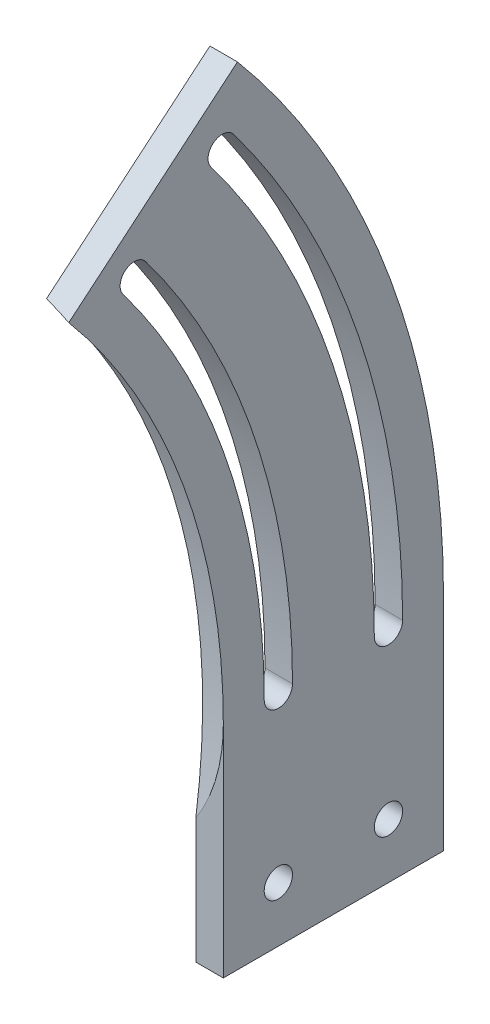
SolidWorks part; units mm, degrees
material "ABS"
ref_plane "Front Plane" through (0, 0, 0) normal (0, 0, 1) x (1, 0, 0)
ref_plane "Top Plane" through (0, 0, 0) normal (0, 1, 0) x (1, 0, 0)
ref_plane "Right Plane" through (0, 0, 0) normal (1, 0, 0) x (0, 0, -1)
sketch "Sketch1" plane through (0, 0, 0) normal (1, 0, 0) x (0, 0, -1)
  line L0 (-1000, 0) -> (49000, 0) construction
  line L1 (0, 0) -> (116.7452, 97.9608) construction
  line L2 (0, 0) -> (71.9216, -52.2541) construction
  line L3 (152.4, 0) -> (152.4, -50.8)
  line L5 (152.4, -50.8) -> (203.2, -50.8)
  line L6 (203.2, -50.8) -> (203.2, 0)
  line L7 (8.1928, 2.9819) -> (218.3104, 79.4585) construction
  line L10 (116.7452, 97.9608) -> (155.6602, 130.6144)
  line L13 (226.7478, 82.5295) -> (220.7808, 80.3576) construction
  line L14 (220.7808, 80.3576) -> (46992.8239, 17103.9891) construction
  arc A0 (152.4, 0) -> (116.7452, 97.9608) centre (0, 0) ccw
  arc A4 (155.6602, 130.6144) -> (203.2, 0) centre (0, 0) cw
  point P9 (226.7478, 82.5295)
  point P15 (0, 0)
  dimension "D1" = 304.8
  dimension "D2" = 40
  dimension "D3" = 36
  dimension "D4" = 50.8
  dimension "D5" = 50.8
  dimension "D6" = 20
  dimension "D9" = 6.35
extrude "Boss-Extrude1" add sketch "Sketch1" along normal blind 6.35
sketch "Sketch2" plane through (6.35, 0, 0) normal (1, 0, 0) x (0, 0, -1)
  line L0 (-1000, 0) -> (49000, 0) construction
  line L1 (0, 0) -> (182.5681, 137.5749) construction
  arc A1 (152.4, 0) -> (116.7452, 97.9608) centre (0, 0) ccw construction
  arc A2 (134.4614, 101.3239) -> (129.2481, 97.3954) centre (131.8547, 99.3597) ccw
  arc A3 (129.2481, 97.3954) -> (161.8361, 0) centre (0, 0) cw
  arc A4 (134.4614, 101.3239) -> (168.3639, 0) centre (0, 0) cw
  arc A5 (161.8361, 0) -> (168.3639, 0) centre (165.1, 0) ccw
  arc A6 (154.7467, 116.61) -> (149.5334, 112.6815) centre (152.1401, 114.6458) ccw
  arc A7 (149.5334, 112.6815) -> (187.2361, 0) centre (0, 0) cw
  arc A8 (154.7467, 116.61) -> (193.7639, 0) centre (0, 0) cw
  arc A9 (152.1401, 114.6458) -> (190.5, 0) centre (0, 0) cw construction
  arc A10 (187.2361, 0) -> (193.7639, 0) centre (190.5, 0) ccw
  point P9 (131.8547, 99.3597)
  point P14 (152.1401, 114.6458)
  point P19 (165.1, 0)
  dimension "D3" = 6.5278
  dimension "D5" = 6.5278
  dimension "D1" = 37
  dimension "D2" = 165.1
  dimension "D4" = 25.4
extrude "Cut-Extrude4" cut sketch "Sketch2" against normal blind 6.35
sketch "Sketch3" plane through (6.35, 0, 0) normal (1, 0, 0) x (0, 0, -1)
  line L0 (165.1, -38.1) -> (190.5, -38.1) construction
  line L1 (152.4, -50.8) -> (165.1, -50.8) construction
  line L2 (152.4, -50.8) -> (152.4, -38.1) construction
  line L3 (152.4, -38.1) -> (165.1, -38.1) construction
  line L4 (165.1, -50.8) -> (165.1, -38.1) construction
  circle A0 centre (165.1, -38.1) radius 3.2639
  circle A1 centre (190.5, -38.1) radius 3.2639
  dimension "D3" = 6.5278
  dimension "D5" = 6.5278
  dimension "D1" = 12.7
  dimension "D2" = 12.7
  dimension "D4" = 25.4
extrude "Cut-Extrude5" cut sketch "Sketch3" against normal blind 6.35
sketch "Sketch6" plane through (6.35, 0, 0) normal (1, 0, 0) x (0, 0, -1)
  line L0 (0, 0) -> (39931.7755, 30090.7512) construction
  line L1 (0, 0) -> (50000, 0) construction
sketch "Sketch7" plane through (0, 0, 0) normal (0, 1, 0) x (1, 0, 0)
  line L0 (0, 0) -> (0, 152.4) construction
  line L1 (0, 152.4) -> (6.35, 152.4) construction
  line L2 (0, 0) -> (-25.4, 0) construction
  line L3 (-25.4, 0) -> (-25.4, 38.1) construction
  line L4 (-25.4, 38.1) -> (-144.0278, 38.1)
  line L5 (-25.4, 38.1) -> (93.2278, 38.1)
  line L6 (-1000, 0) -> (49000, 0) construction
  arc A0 (93.2278, 38.1) -> (-144.0278, 38.1) centre (-25.4, 38.1) ccw
  dimension "D1" = 152.4
  dimension "D2" = 6.35
  dimension "D3" = 25.4
  dimension "D4" = 38.1
revolve "Cut-Revolve1" cut sketch "Sketch7" angle 360 about L6
sketch "Sketch8" plane through (6.35, 0, 0) normal (1, 0, 0) x (0, 0, -1)
  line L0 (0, 0) -> (177.8, 0)
  line L1 (0, 0) -> (152.1401, 114.6458)
  dimension "D1" = 177.8
